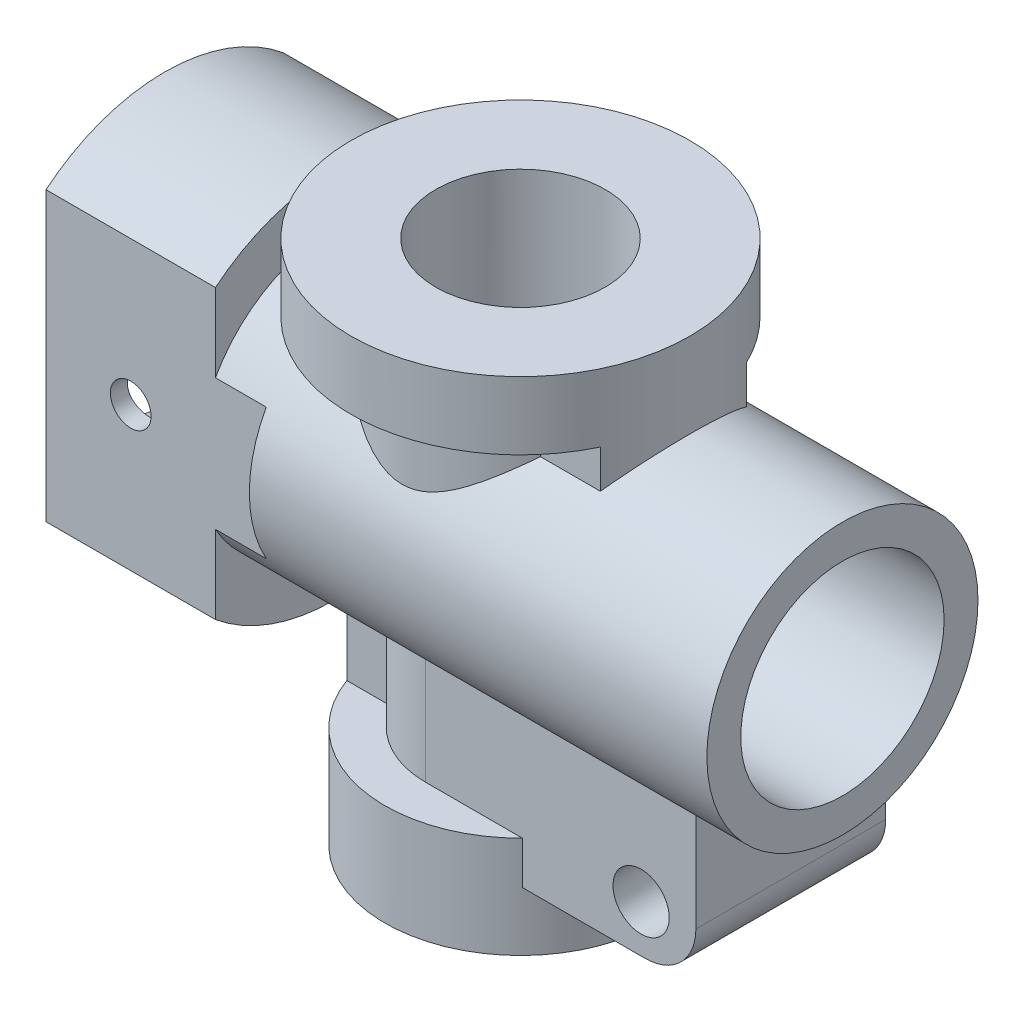
SolidWorks part; units mm, degrees
ref_plane "前视基准面" through (0, 0, 0) normal (0, 0, 1) x (1, 0, 0)
ref_plane "上视基准面" through (0, 0, 0) normal (0, 1, 0) x (1, 0, 0)
ref_plane "右视基准面" through (0, 0, 0) normal (1, 0, 0) x (0, 0, -1)
sketch "草图1" plane through (0, 0, 0) normal (1, 0, 0) x (0, 0, -1)
  circle A0 centre (0, 0) radius 40
extrude "凸台-拉伸1" add sketch "草图1" along normal blind 150
sketch "草图2" plane through (0, 0, 0) normal (1, 0, 0) x (0, 0, -1)
  circle A0 centre (0, 0) radius 55
extrude "凸台-拉伸2" add sketch "草图2" against normal blind 50
sketch "草图3" plane through (150, 0, 0) normal (1, 0, 0) x (0, 0, -1)
  circle A0 centre (0, 0) radius 30
extrude "切除-拉伸2" cut sketch "草图3" against normal blind 200
sketch "草图5" plane through (0, 0, 0) normal (0, 0, 1) x (1, 0, 0)
  circle A0 centre (-25, 0) radius 6
extrude "切除-拉伸3" cut sketch "草图5" along normal blind 134 and the other way blind 106
sketch "草图7" plane through (0, 0, 0) normal (0, 1, 0) x (1, 0, 0)
  line L0 (82.442, 21.5486) -> (100.1183, 21.5486)
  line L1 (82.442, -21.5486) -> (100.1183, -21.5486)
  line L2 (27.558, 21.5486) -> (9.8817, 21.5486)
  line L3 (27.558, -21.5486) -> (9.8817, -21.5486)
  arc A0 (100.1183, -21.5486) -> (100.1183, 21.5486) centre (55, 0) ccw
  arc A1 (27.558, -21.5486) -> (82.442, -21.5486) centre (55, 0) ccw
  arc A2 (82.442, 21.5486) -> (27.558, 21.5486) centre (55, 0) ccw
  arc A3 (9.8817, 21.5486) -> (9.8817, -21.5486) centre (55, 0) ccw
extrude "凸台-拉伸3" add sketch "草图7" along normal blind 45
sketch "草图15" plane through (0, 45, 0) normal (0, 1, 0) x (1, 0, 0)
  circle A0 centre (55, 0) radius 50
extrude "凸台-拉伸5" add sketch "草图15" along normal blind 20
sketch "草图16" plane through (0, 0, 0) normal (0, 1, 0) x (1, 0, 0)
  line L0 (30.5392, 13.6261) -> (17.3924, 13.6261)
  line L1 (17.3924, -13.6261) -> (30.5392, -13.6261)
  line L2 (79.4608, -13.6261) -> (92.6076, -13.6261)
  line L3 (79.4608, 13.6261) -> (92.6076, 13.6261)
  arc A0 (17.3924, 13.6261) -> (17.3924, -13.6261) centre (55, 0) ccw
  arc A1 (30.5392, -13.6261) -> (79.4608, -13.6261) centre (55, 0) ccw
  arc A2 (92.6076, -13.6261) -> (92.6076, 13.6261) centre (55, 0) ccw
  arc A3 (79.4608, 13.6261) -> (30.5392, 13.6261) centre (55, 0) ccw
extrude "凸台-拉伸6" add sketch "草图16" against normal blind 59.9919
sketch "草图17" plane through (0, -59.9919, 0) normal (0, -1, 0) x (1, 0, 0)
  circle A0 centre (55, 0) radius 40
extrude "凸台-拉伸7" add sketch "草图17" along normal blind 30
sketch "草图18" plane through (0, -89.9919, 0) normal (0, -1, 0) x (1, 0, 0)
  circle A0 centre (55, 0) radius 26
extrude "切除-拉伸25" cut sketch "草图18" against normal blind 30
sketch "草图19" plane through (0, -59.9919, 0) normal (0, -1, 0) x (1, 0, 0)
  circle A0 centre (55, 0) radius 17
extrude "切除-拉伸26" cut sketch "草图19" against normal blind 51
sketch "草图20" plane through (0, 0, 0) normal (1, 0, 0) x (0, 0, -1)
  circle A0 centre (0, 0) radius 30
extrude "切除-拉伸27" cut sketch "草图20" against normal blind 99 and the other way blind 170
sketch "草图21" plane through (0, 65, 0) normal (0, 1, 0) x (1, 0, 0)
  circle A0 centre (55, 0) radius 25
extrude "切除-拉伸28" cut sketch "草图21" against normal blind 60
sketch "草图22" plane through (0, 0, 0) normal (0, 0, 1) x (1, 0, 0)
  line L1 (119.7565, -72.6158) -> (55, -72.6158)
  line L2 (134.7565, -57.6158) -> (134.7565, -17.6158)
  line L3 (134.7565, -17.6158) -> (55, -17.6158)
  line L4 (55, -72.6158) -> (55, -17.6158)
  arc A0 (119.7565, -72.6158) -> (134.7565, -57.6158) centre (119.7565, -57.6158) ccw
  dimension "D1" = 15
extrude "凸台-拉伸8" add sketch "草图22" along normal blind 28 and the other way blind 28
sketch "草图23" plane through (0, 0, 28) normal (0, 0, 1) x (1, 0, 0)
  circle A0 centre (118.5992, -58.7022) radius 8.2947
  point P2 (0, 0)
extrude "切除-拉伸29" cut sketch "草图23" against normal blind 70
sketch "草图24" plane through (0, 0, 0) normal (0, 1, 0) x (1, 0, 0)
  line L1 (-70, -60) -> (15, -60)
  line L2 (-70, -60) -> (-70, -35)
  line L3 (-70, -35) -> (15, -35)
  line L4 (15, -60) -> (15, -35)
extrude "切除-拉伸30" cut sketch "草图24" against normal up to surface and the other way blind 70 up to face at (-19.1515, -1.3399, -54.9837)
sketch "草图25" plane through (0, 0, 0) normal (0, 1, 0) x (1, 0, 0)
  line L1 (-70, 60) -> (15, 60)
  line L2 (-70, 60) -> (-70, 35)
  line L3 (-70, 35) -> (15, 35)
  line L4 (15, 60) -> (15, 35)
extrude "切除-拉伸31" cut sketch "草图25" against normal blind 70 and the other way blind 70
sketch "草图26" plane through (0, -89.9919, 0) normal (0, -1, 0) x (1, 0, 0)
  circle A0 centre (55, 0) radius 26
extrude "切除-拉伸32" cut sketch "草图26" against normal blind 30
sketch "草图27" plane through (0, -59.9919, 0) normal (0, -1, 0) x (1, 0, 0)
  line L0 (55, -17) -> (55, 17) construction
  circle A0 centre (55, 0) radius 17
extrude "切除-拉伸33" cut sketch "草图27" against normal blind 55
sketch "草图29" plane through (0, 0, 0) normal (1, 0, 0) x (0, 0, -1)
  circle A0 centre (0, 0) radius 30
extrude "切除-拉伸34" cut sketch "草图29" against normal blind 195 and the other way blind 417
